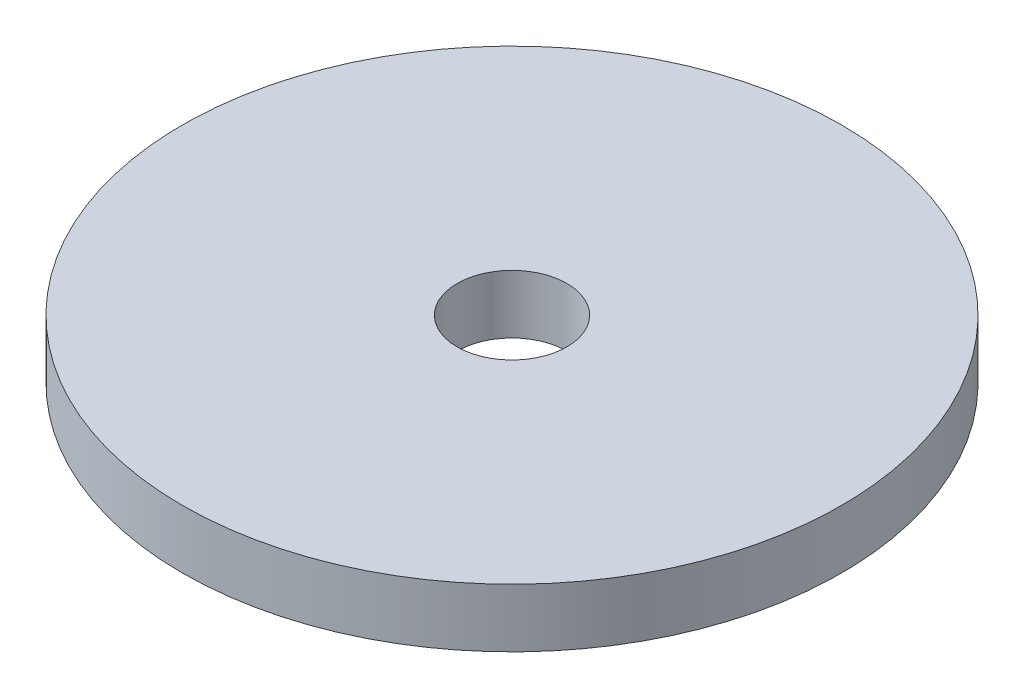
SolidWorks part; units mm, degrees
ref_plane "Front Plane" through (0, 0, 0) normal (0, 0, 1) x (1, 0, 0)
ref_plane "Top Plane" through (0, 0, 0) normal (0, 1, 0) x (1, 0, 0)
ref_plane "Right Plane" through (0, 0, 0) normal (1, 0, 0) x (0, 0, -1)
sketch "Sketch1" plane through (0, 0, 0) normal (0, 1, 0) x (1, 0, 0)
  circle A0 centre (0, 0) radius 22.5
  circle A1 centre (0, 0) radius 3.75
extrude "Boss-Extrude1" add sketch "Sketch1" along normal blind 4
